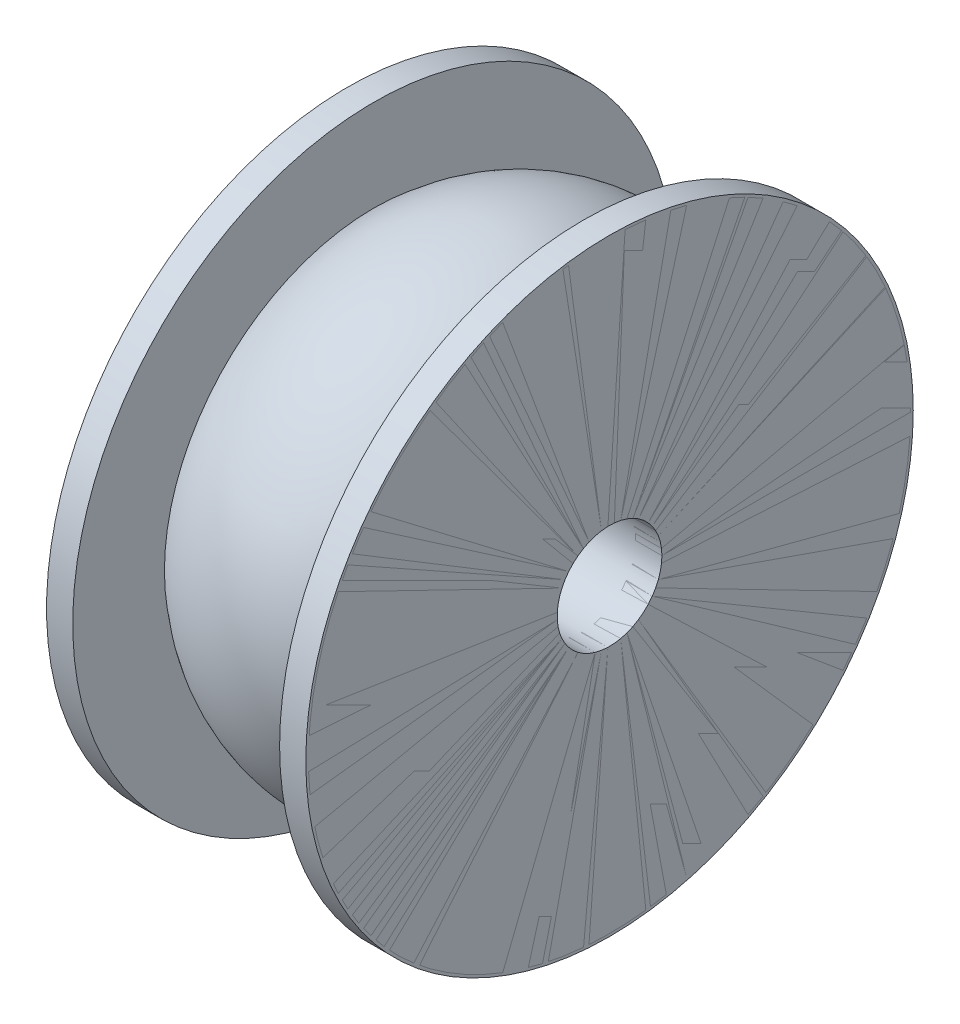
SolidWorks part; units mm, degrees
ref_plane "Front Plane" through (0, 0, 0) normal (0, 0, 1) x (1, 0, 0)
ref_plane "Top Plane" through (0, 0, 0) normal (0, 1, 0) x (1, 0, 0)
ref_plane "Right Plane" through (0, 0, 0) normal (1, 0, 0) x (0, 0, -1)
sketch "Sketch1" plane through (0, 0, 0) normal (1, 0, 0) x (0, 0, -1)
  circle A0 centre (0, 0) radius 5.77
  circle A1 centre (0, 0) radius 4.5
  circle A2 centre (0, 0) radius 1
  dimension "D1" = 2
  dimension "D2" = 9
  dimension "D3" = 11.54
sketch "Sketch6" plane through (0, 0, 0) normal (1, 0, 0) x (0, 0, -1)
  circle A0 centre (0, 0) radius 5.75
  dimension "D1" = 11.5
extrude "Boss-Extrude4" add sketch "Sketch6" against normal blind 0.5
ref_plane "Plane1" through (2, 0, 0) normal (1, 0, 0) x (0, 0, -1)
sketch "Sketch7" plane through (0, 0, 0) normal (0, 1, 0) x (1, 0, 0)
  line L0 (0, -1) -> (4, -1)
  line L1 (0, 0) -> (4, 0)
  line L3 (4, 0) -> (4, -3.9993)
  line L6 (4, -3.9993) -> (0, -3.9993)
  line L7 (0, -5.75) -> (0, 5.75) construction
  line L9 (0, -3.9993) -> (0, 0)
  arc A0 (0, -3.9993) -> (4, -3.9993) centre (2, -1.7632) ccw
  dimension "D2" = 3
  dimension "D1" = 4
  dimension "D3" = 1
revolve "Revolve1" add sketch "Sketch7" angle 360 about L1
mirror "Mirror1" about plane through (2, 0, 0) normal (1, 0, 0) of "Boss-Extrude4"
ref_plane "Plane2" through (4, 0, 0) normal (1, 0, 0) x (0, 0, -1)
sketch "Sketch21" plane through (4, 0, 0) normal (1, 0, 0) x (0, 0, -1)
  circle A0 centre (0, 0) radius 5.8
  dimension "D1" = 11.6
extrude "Boss-Extrude5" add sketch "Sketch21" along normal blind 0.5 separate body
ref_plane "Plane3" through (4.5, 0, 0) normal (1, 0, 0) x (0, 0, -1)
sketch "Sketch22" plane through (4.5, 0, 0) normal (1, 0, 0) x (0, 0, -1)
  circle A0 centre (0, 0) radius 1
  dimension "D1" = 2
extrude "Cut-Extrude1" cut sketch "Sketch22" against normal through all
